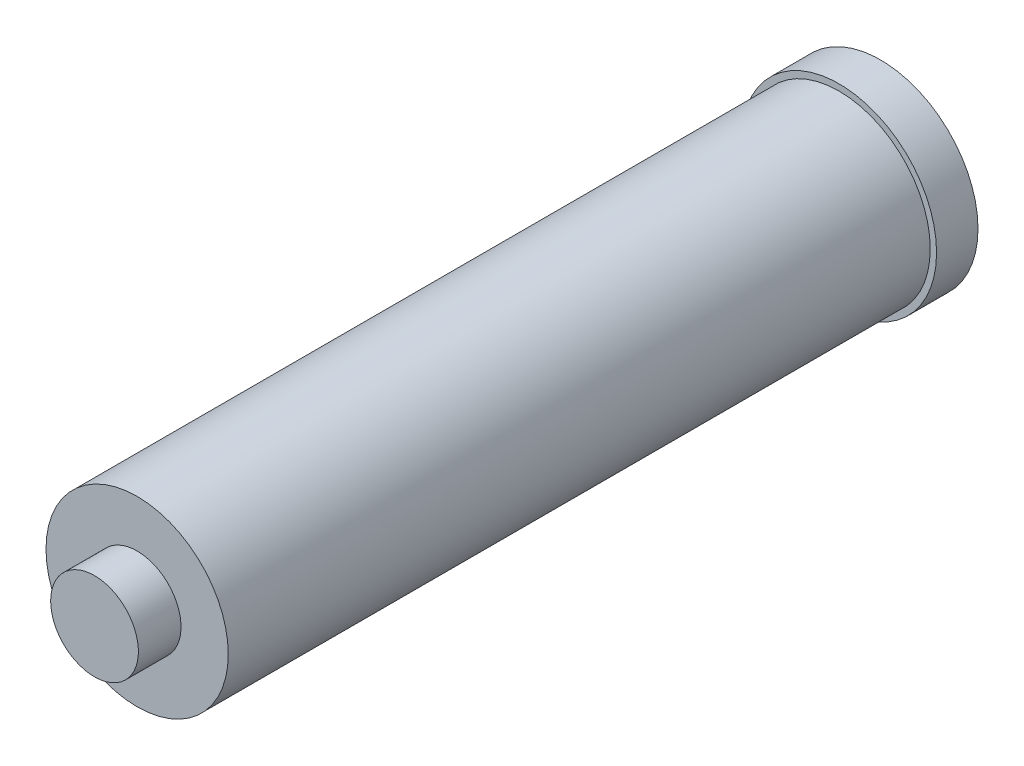
SolidWorks part; units mm, degrees
ref_plane "Front Plane" through (0, 0, 0) normal (0, 0, 1) x (1, 0, 0)
ref_plane "Top Plane" through (0, 0, 0) normal (0, 1, 0) x (1, 0, 0)
ref_plane "Right Plane" through (0, 0, 0) normal (1, 0, 0) x (0, 0, -1)
sketch "Sketch3" plane through (0, 0, 0) normal (0, 0, 1) x (1, 0, 0)
  circle A0 centre (0, 0) radius 19
extrude "Boss-Extrude1" add sketch "Sketch3" along normal blind 146.35
sketch "Sketch4" plane through (0, 0, 0) normal (0, 0, -1) x (-1, 0, 0)
  circle A0 centre (0, 0) radius 20.32
extrude "Boss-Extrude2" add sketch "Sketch4" along normal blind 8.636
sketch "Sketch5" plane through (0, 0, 146.35) normal (0, 0, 1) x (1, 0, 0)
  circle A0 centre (0, 0) radius 9.144
extrude "Boss-Extrude3" add sketch "Sketch5" along normal blind 8.89
